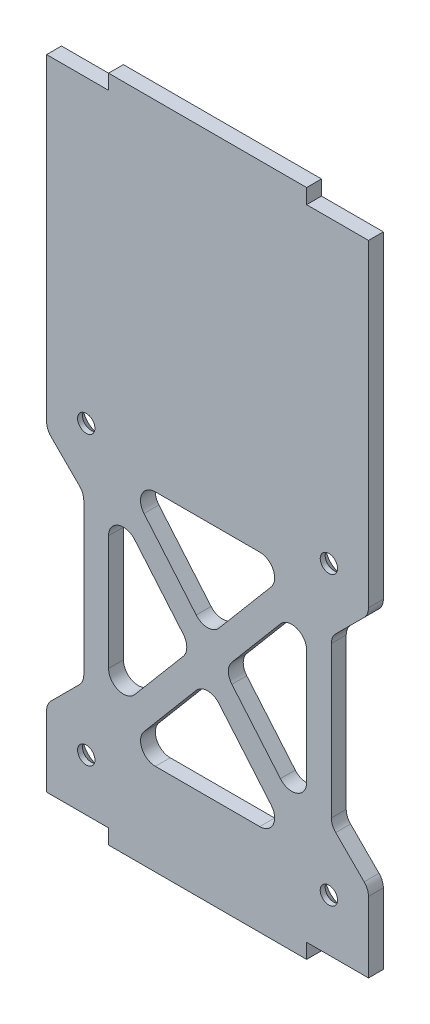
SolidWorks part; units mm, degrees
material "ABS"
ref_plane "Спереди" through (0, 0, 0) normal (0, 0, 1) x (1, 0, 0)
ref_plane "Сверху" through (0, 0, 0) normal (0, 1, 0) x (1, 0, 0)
ref_plane "Справа" through (0, 0, 0) normal (1, 0, 0) x (0, 0, -1)
sketch "Эскиз1" plane through (0, 0, 0) normal (0, 0, 1) x (1, 0, 0)
  line L0 (-32.5, 0) -> (32.5, 0) construction
  line L1 (-32.5, -64.5) -> (32.5, -64.5)
  line L2 (-32.5, -64.5) -> (-32.5, 64.5)
  line L3 (-32.5, 64.5) -> (32.5, 64.5)
  line L4 (32.5, -64.5) -> (32.5, 64.5)
  line L5 (-32.5, -64.5) -> (32.5, 64.5) construction
  line L6 (-32.5, 64.5) -> (32.5, -64.5) construction
  line L7 (-20, 61.5) -> (20, 61.5)
  line L8 (-20, 61.5) -> (-20, 67.5)
  line L9 (-20, 67.5) -> (20, 67.5)
  line L10 (20, 61.5) -> (20, 67.5)
  line L11 (-20, 61.5) -> (20, 67.5) construction
  line L12 (-20, 67.5) -> (20, 61.5) construction
  line L13 (-20, -67.5) -> (20, -61.5) construction
  line L14 (-20, -61.5) -> (20, -67.5) construction
  line L15 (20, -61.5) -> (20, -67.5)
  line L16 (-20, -67.5) -> (20, -67.5)
  line L17 (-20, -61.5) -> (-20, -67.5)
  line L18 (-20, -61.5) -> (20, -61.5)
  point P0 (0, 0)
  point P6 (0, 64.5)
  point P17 (0, -64.5)
  dimension "D1" = 3
  dimension "D2" = 40
  dimension "D3" = 12.5
  dimension "D4" = 129
extrude "Бобышка-Вытянуть1" add sketch "Эскиз1" along normal blind 3 contours L10 L7 L8 L3 L2 L1 L4 | L7 L10 L3 L8 | L3 L10 L9 L8 | L18 L17 L1 L15 | L1 L17 L16 L15
sketch "Эскиз2" plane through (0, 0, 3) normal (0, 0, 1) x (1, 0, 0)
  line L0 (0, -62.5) -> (0, 67.5) construction
  line L2 (-20, 67.5) -> (20, 67.5) construction
  line L4 (-24.5, -54) -> (24.5, -54) construction
  line L5 (-24.5, -54) -> (-24.5, 4) construction
  line L6 (-24.5, 4) -> (24.5, 4) construction
  line L7 (24.5, -54) -> (24.5, 4) construction
  line L8 (-24.5, -54) -> (24.5, 4) construction
  line L9 (-24.5, 4) -> (24.5, -54) construction
  circle A0 centre (-24.5, 4) radius 1.75
  circle A1 centre (24.5, 4) radius 1.75
  circle A2 centre (24.5, -54) radius 1.75
  circle A3 centre (-24.5, -54) radius 1.75
  point P6 (0, -25)
  dimension "D4" = 3.5
  dimension "D1" = 49
  dimension "D2" = 58
  dimension "D3" = 25
extrude "Вырез-Вытянуть1" cut sketch "Эскиз2" against normal blind 10
chamfer "Фаска1" distance 2 angle 45 4 edges at (-22.75, -54, 0) (-22.75, 4, 0) (26.25, 4, 0) (26.25, -54, 0)
sketch "Эскиз3" plane through (0, 0, 0) normal (0, 0, -1) x (-1, 0, 0)
  line L0 (0, 67.5) -> (0, -67.5) construction
  line L1 (20, 67.5) -> (-20, 67.5) construction
  line L2 (20, -67.5) -> (-20, -67.5) construction
  line L3 (32.5, -1) -> (25, -8.5)
  line L4 (32.5, -64.5) -> (32.5, 64.5) construction
  line L5 (25, -8.5) -> (25, -41.5)
  line L6 (25, -41.5) -> (32.5, -49)
  line L7 (32.5, -1) -> (35.9276, -1)
  line L8 (35.9276, -1) -> (35.9276, -49)
  line L9 (35.9276, -49) -> (32.5, -49)
  line L10 (-35.9276, -49) -> (-32.5, -49)
  line L11 (-35.9276, -1) -> (-35.9276, -49)
  line L12 (-32.5, -1) -> (-35.9276, -1)
  line L13 (-25, -41.5) -> (-32.5, -49)
  line L14 (-25, -8.5) -> (-25, -41.5)
  line L15 (-32.5, -1) -> (-25, -8.5)
  line L16 (16.1514, -44.1179) -> (-24.5, 4) construction
  line L17 (0, -21.1261) -> (-17.0031, -1)
  line L18 (17.0031, -1) -> (0, -21.1261)
  line L19 (20, -5.2004) -> (3.2727, -25)
  line L20 (20, -44.7996) -> (3.2727, -25)
  line L21 (17.0031, -49) -> (0, -28.8739)
  line L22 (17.0031, -1) -> (-17.0031, -1)
  line L23 (25, -25) -> (-25, -25) construction
  line L24 (17.0031, -49) -> (-17.0031, -49)
  line L25 (20, -5.2004) -> (20, -44.7996)
  line L26 (-20, -5.2004) -> (-20, -44.7996)
  line L39 (21.5834, -46.6738) -> (-22.5903, 5.6134) construction
  line L40 (17.764, -49.9006) -> (-26.4097, 2.3866) construction
  line L41 (0, -28.8739) -> (-17.0031, -49)
  line L42 (-3.2727, -25) -> (-20, -5.2004)
  line L43 (-3.2727, -25) -> (-20, -44.7996)
  line L44 (19.6737, -48.2872) -> (-24.5, 4) construction
  dimension "D1" = 135
  dimension "D2" = 5
  dimension "D3" = 5
  dimension "D4" = 7.5
  dimension "D9" = 5
  dimension "D5" = 5
  dimension "D7" = 2.5
  dimension "D8" = 2.5
extrude "Вырез-Вытянуть2" cut sketch "Эскиз3" against normal blind 10
fillet "Скругление1" radius 3 4 edges at (-32.5, -1, 1.5) (-25, -8.5, 1.5) (-32.5, -49, 1.5) (-25, -41.5, 1.5)
fillet "Скругление2" radius 3 4 edges at (32.5, -49, 1.5) (32.5, -1, 1.5) (25, -8.5, 1.5) (25, -41.5, 1.5)
fillet "Скругление3" radius 3 12 edges at (20, -44.7996, 1.5) (20, -5.2004, 1.5) (17.0031, -1, 1.5) (-17.0031, -1, 1.5) (-20, -5.2004, 1.5) (-20, -44.7996, 1.5) (3.2727, -25, 1.5) (0, -21.1261, 1.5) (-3.2727, -25, 1.5) (0, -28.8739, 1.5) (17.0031, -49, 1.5) (-17.0031, -49, 1.5)
